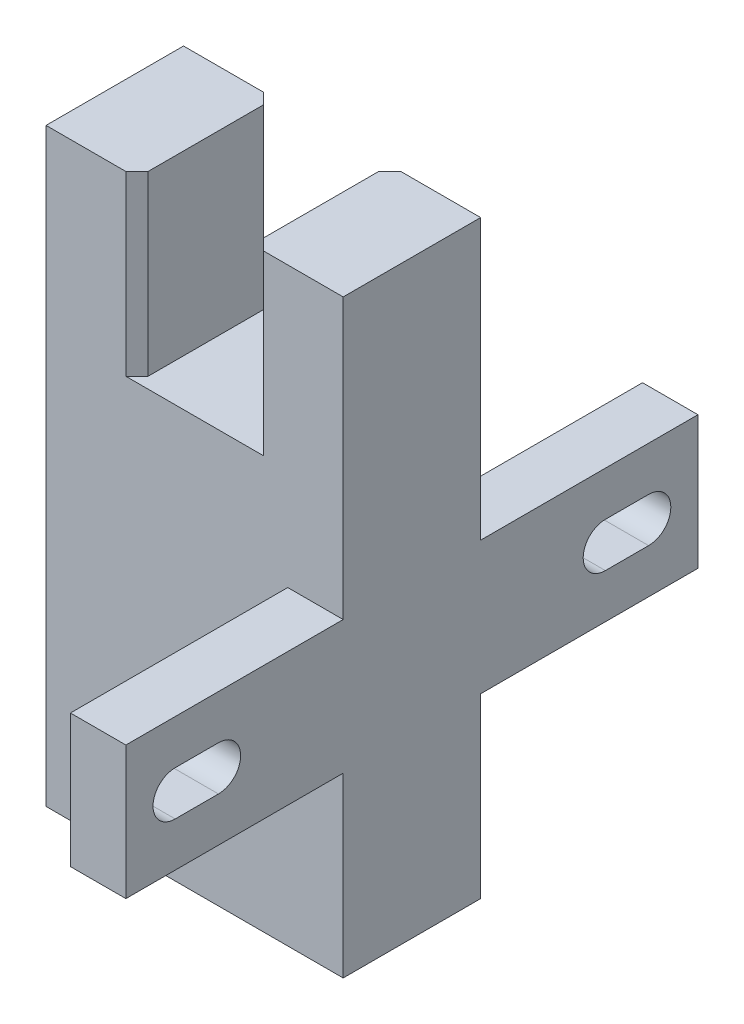
SolidWorks part; units mm, degrees
ref_plane "前视基准面" through (0, 0, 0) normal (0, 0, 1) x (1, 0, 0)
ref_plane "上视基准面" through (0, 0, 0) normal (0, 1, 0) x (1, 0, 0)
ref_plane "右视基准面" through (0, 0, 0) normal (1, 0, 0) x (0, 0, -1)
sketch "草图1" plane through (0, 0, 0) normal (0, 0, 1) x (1, 0, 0)
  line L8 (0, 0) -> (0, 1.5909) construction
  line L9 (2.6, 0.7955) -> (-2.6, 0.7955)
  line L10 (-2.6, 0.7955) -> (-2.6, 8.7955)
  line L11 (-2.6, 8.7955) -> (-6.7, 8.7955)
  line L12 (-6.7, 8.7955) -> (-6.7, -17.8045)
  line L13 (-6.7, -17.8045) -> (6.7, -17.8045)
  line L14 (6.7, 8.7955) -> (6.7, -17.8045)
  line L15 (2.6, 0.7955) -> (2.6, 8.7955)
  line L16 (2.6, 8.7955) -> (6.7, 8.7955)
  point P13 (0, -17.8045)
  point P14 (0, 0.7955)
  dimension "D1" = 13.4
  dimension "D2" = 5.2
  dimension "D3" = 26.6
  dimension "D4" = 8
extrude "凸台-拉伸1" add sketch "草图1" along normal blind 6.2
sketch "草图2" plane through (0, 0, 6.2) normal (0, 0, 1) x (1, 0, 0)
  line L0 (6.7, -17.8045) -> (6.7, 8.7955) construction
  line L1 (6.7, -9.8045) -> (4.2, -9.8045)
  line L2 (6.7, -9.8045) -> (6.7, -3.8045)
  line L3 (6.7, -3.8045) -> (4.2, -3.8045)
  line L4 (4.2, -9.8045) -> (4.2, -3.8045)
  line L5 (6.7, 8.7955) -> (2.6, 8.7955) construction
  dimension "D1" = 2.5
  dimension "D2" = 6
  dimension "D3" = 12.6
extrude "凸台-拉伸2" add sketch "草图2" along normal blind 9.8
sketch "草图3" plane through (0, 0, 0) normal (0, 0, -1) x (-1, 0, 0)
  line L0 (-6.7, -17.8045) -> (-6.7, 8.7955) construction
  line L1 (-6.7, -3.8045) -> (-4.2, -3.8045)
  line L2 (-6.7, -3.8045) -> (-6.7, -9.8045)
  line L3 (-6.7, -9.8045) -> (-4.2, -9.8045)
  line L4 (-4.2, -3.8045) -> (-4.2, -9.8045)
  line L5 (-6.7, 8.7955) -> (-2.6, 8.7955) construction
  dimension "D1" = 2.5
  dimension "D2" = 12.6
  dimension "D3" = 6
extrude "凸台-拉伸3" add sketch "草图3" along normal blind 9.8
sketch "草图5" plane through (6.7, 0, 0) normal (1, 0, 0) x (0, 0, -1)
  line L2 (-13.7757, -6.8045) -> (-11.8243, -6.8045) construction
  line L3 (-13.7757, -5.8045) -> (-11.8243, -5.8045)
  line L4 (-13.7757, -7.8045) -> (-11.8243, -7.8045)
  line L5 (-3.1, 8.7955) -> (-3.1, -17.8045) construction
  line L6 (-6.2, 8.7955) -> (0, 8.7955) construction
  line L7 (-6.2, -17.8045) -> (0, -17.8045) construction
  line L8 (7.5757, -6.8045) -> (5.6243, -6.8045) construction
  line L9 (7.5757, -5.8045) -> (5.6243, -5.8045)
  line L10 (7.5757, -7.8045) -> (5.6243, -7.8045)
  arc A0 (-13.7757, -5.8045) -> (-13.7757, -7.8045) centre (-13.7757, -6.8045) ccw
  arc A1 (-11.8243, -7.8045) -> (-11.8243, -5.8045) centre (-11.8243, -6.8045) ccw
  arc A2 (7.5757, -5.8045) -> (7.5757, -7.8045) centre (7.5757, -6.8045) cw
  arc A3 (5.6243, -7.8045) -> (5.6243, -5.8045) centre (5.6243, -6.8045) cw
  point P0 (-12.8, -6.8045)
  point P15 (6.6, -6.8045)
  dimension "D2" = 1
  dimension "D1" = 19.4
extrude "切除-拉伸1" cut sketch "草图5" against normal through all
chamfer "倒角1" distance 0.5 angle 45 4 edges at (2.6, 4.7955, 0) (2.6, 4.7955, 6.2) (-2.6, 4.7955, 0) (-2.6, 4.7955, 6.2)
